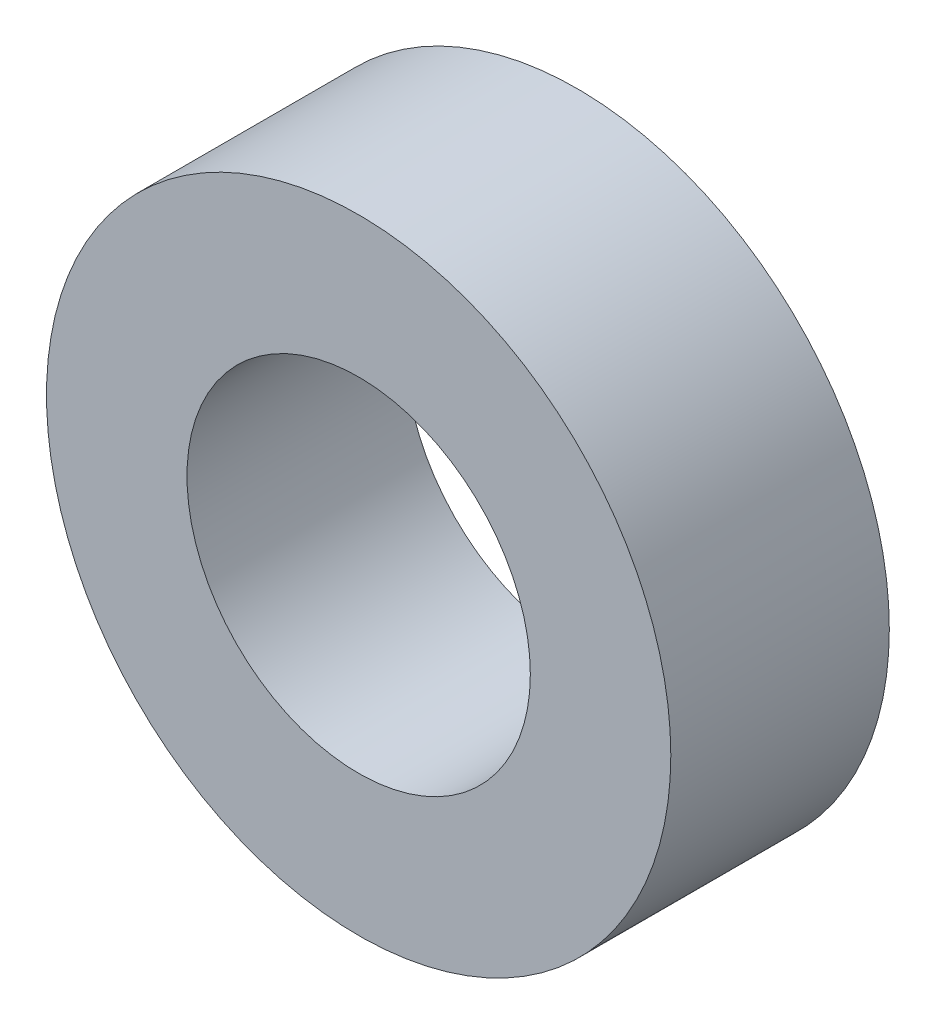
SolidWorks part; units mm, degrees
ref_plane "前视基准面" through (0, 0, 0) normal (0, 0, 1) x (1, 0, 0)
ref_plane "上视基准面" through (0, 0, 0) normal (0, 1, 0) x (1, 0, 0)
ref_plane "右视基准面" through (0, 0, 0) normal (1, 0, 0) x (0, 0, -1)
other "Configuration Table"
sketch "Profile_1" plane through (0, 0, 0) normal (0, 0, 1) x (1, 0, 0)
  circle A0 centre (0, 0) radius 50
  circle A1 centre (0, 0) radius 27.5
extrude "Tyre_swept_envelope" add sketch "Profile_1" along normal blind 35 from offset 17.5
